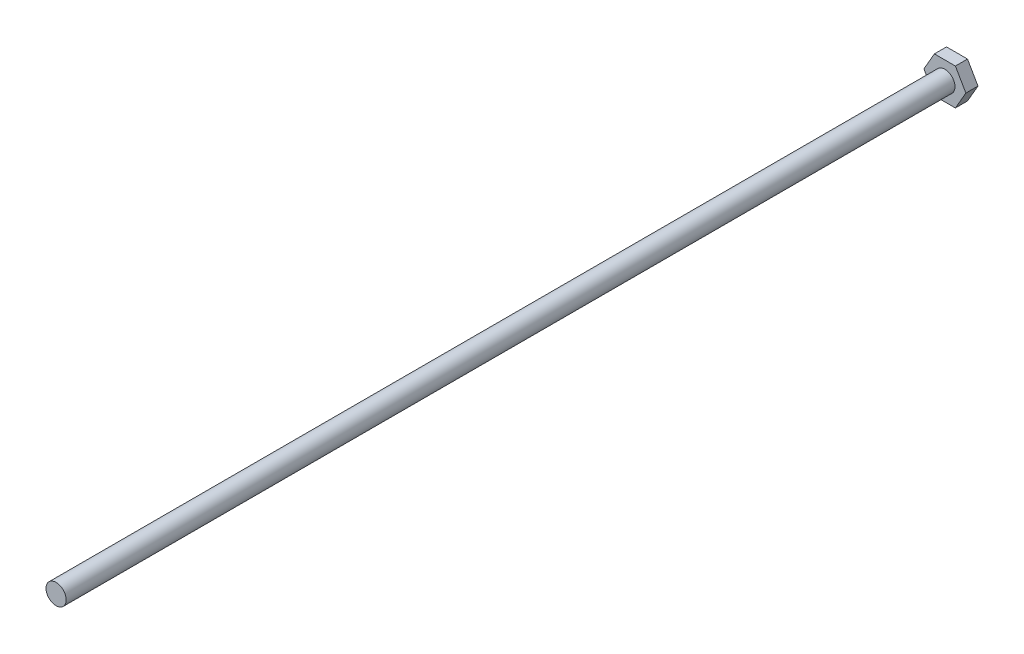
SolidWorks part; units mm, degrees
ref_plane "Plano frontal" through (0, 0, 0) normal (0, 0, 1) x (1, 0, 0)
ref_plane "Plano superior" through (0, 0, 0) normal (0, 1, 0) x (1, 0, 0)
ref_plane "Plano direito" through (0, 0, 0) normal (1, 0, 0) x (0, 0, -1)
sketch "Esboço1" plane through (0, 0, 0) normal (0, 0, 1) x (1, 0, 0)
  circle A0 centre (0, 0) radius 2.5
  dimension "D1" = 5
extrude "Extrusão1" add sketch "Esboço1" along normal blind 220
cosmetic thread "Representação de rosca1" parameters "D1"=20, "D2"=3.75
sketch "Esboço2" plane through (0, 0, 0) normal (0, 0, -1) x (-1, 0, 0)
  line L1 (5.1962, 0) -> (2.5981, 4.5)
  line L2 (2.5981, 4.5) -> (-2.5981, 4.5)
  line L3 (-2.5981, 4.5) -> (-5.1962, 0)
  line L4 (-5.1962, 0) -> (-2.5981, -4.5)
  line L5 (-2.5981, -4.5) -> (2.5981, -4.5)
  line L6 (2.5981, -4.5) -> (5.1962, 0)
  circle A0 centre (0, 0) radius 4.5 construction
  dimension "D1" = 9
extrude "Extrusão2" add sketch "Esboço2" along normal blind 3
